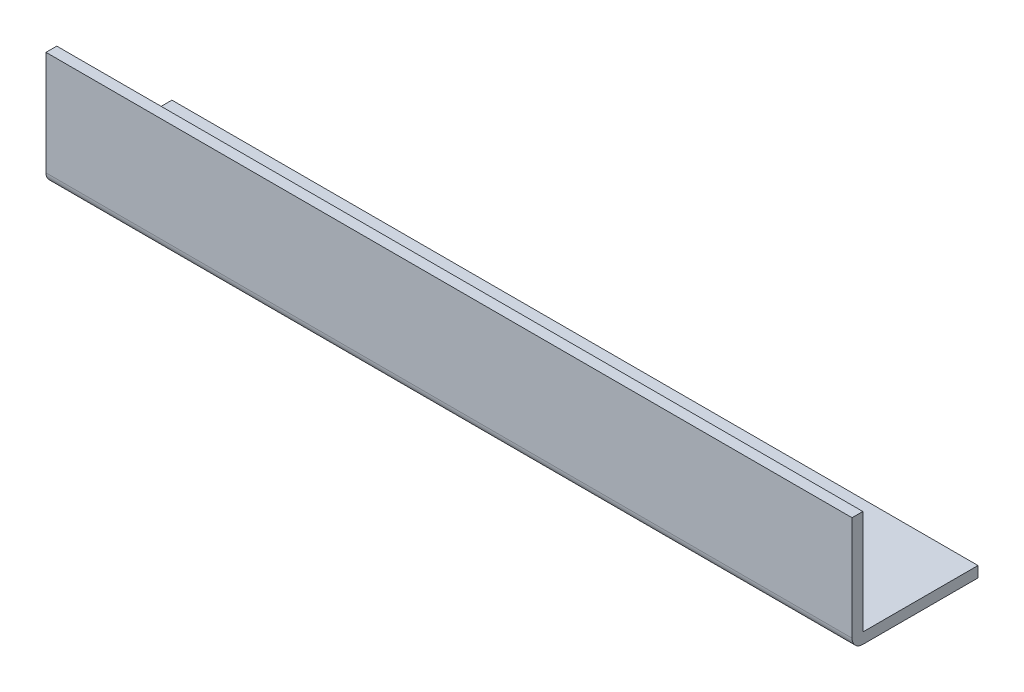
SolidWorks part; units mm, degrees
ref_plane "Front Plane" through (0, 0, 0) normal (0, 0, 1) x (1, 0, 0)
ref_plane "Top Plane" through (0, 0, 0) normal (0, 1, 0) x (1, 0, 0)
ref_plane "Right Plane" through (0, 0, 0) normal (1, 0, 0) x (0, 0, -1)
sketch "Sketch1" plane through (0, 0, 0) normal (0, 1, 0) x (1, 0, 0)
  line L1 (0, 0) -> (177.8, 0)
  line L2 (0, 0) -> (0, 25.4)
  line L3 (0, 25.4) -> (177.8, 25.4)
  line L4 (177.8, 0) -> (177.8, 25.4)
  dimension "D1" = 25.4
  dimension "D2" = 177.8
extrude "Boss-Extrude1" add sketch "Sketch1" along normal blind 2.3813
sketch "Sketch2" plane through (0, 0, 0) normal (0, 0, 1) x (1, 0, 0)
  line L0 (0, 0) -> (177.8, 0) construction
  line L1 (0, 0) -> (177.8, 0)
  line L2 (0, 0) -> (0, 25.4)
  line L3 (0, 25.4) -> (177.8, 25.4)
  line L4 (177.8, 0) -> (177.8, 25.4)
  dimension "D1" = 25.4
extrude "Boss-Extrude2" add sketch "Sketch2" along normal blind 2.3813
fillet "Fillet1" radius 2.3813 1 edges at (88.9, 0, 2.3813)
